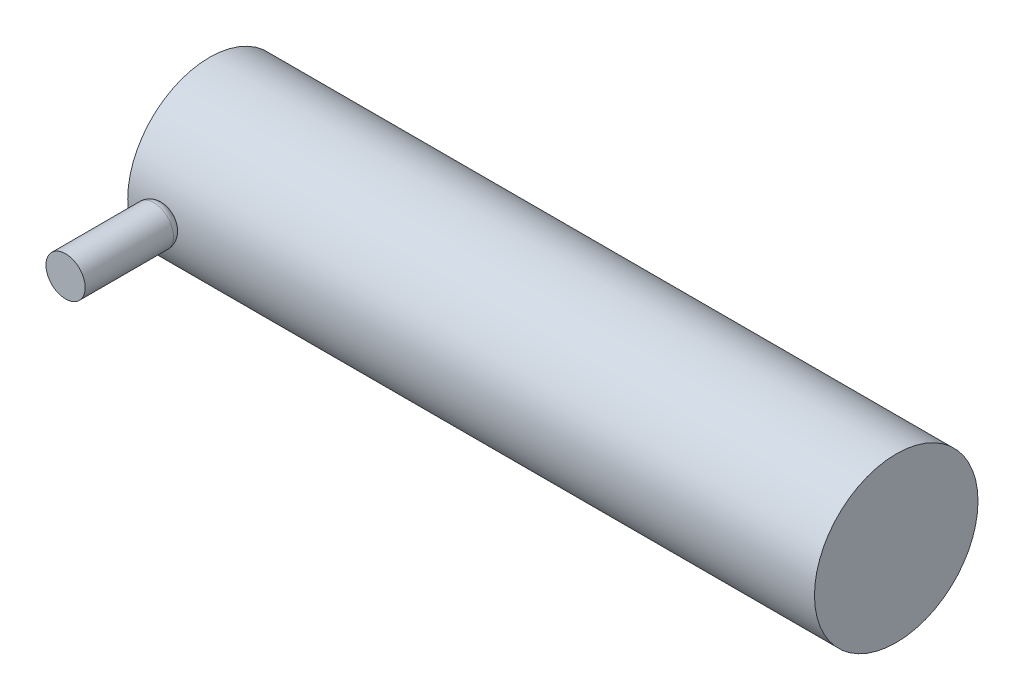
SolidWorks part; units mm, degrees
material "AISI 1020"
ref_plane "Front Plane" through (0, 0, 0) normal (0, 0, 1) x (1, 0, 0)
ref_plane "Top Plane" through (0, 0, 0) normal (0, 1, 0) x (1, 0, 0)
ref_plane "Right Plane" through (0, 0, 0) normal (1, 0, 0) x (0, 0, -1)
sketch "Sketch1" plane through (0, 0, 0) normal (1, 0, 0) x (0, 0, -1)
  circle A0 centre (0, 0) radius 25
  dimension "D1" = 50
extrude "Boss-Extrude1" add sketch "Sketch1" against normal blind 210
sketch "Sketch2" plane through (0, 0, 0) normal (0, 0, 1) x (1, 0, 0)
  line L0 (-210, 25) -> (-210, -25) construction
  line L2 (-210, -25) -> (0, -25) construction
  circle A0 centre (-199, 0) radius 6
  dimension "D1" = 12
  dimension "D2" = 5
  dimension "D3" = 25
extrude "Boss-Extrude2" add sketch "Sketch2" along normal blind 30 from offset 25 separate body
fillet "Fillet1" radius 3 1 edges at (-193, 0, 25)
